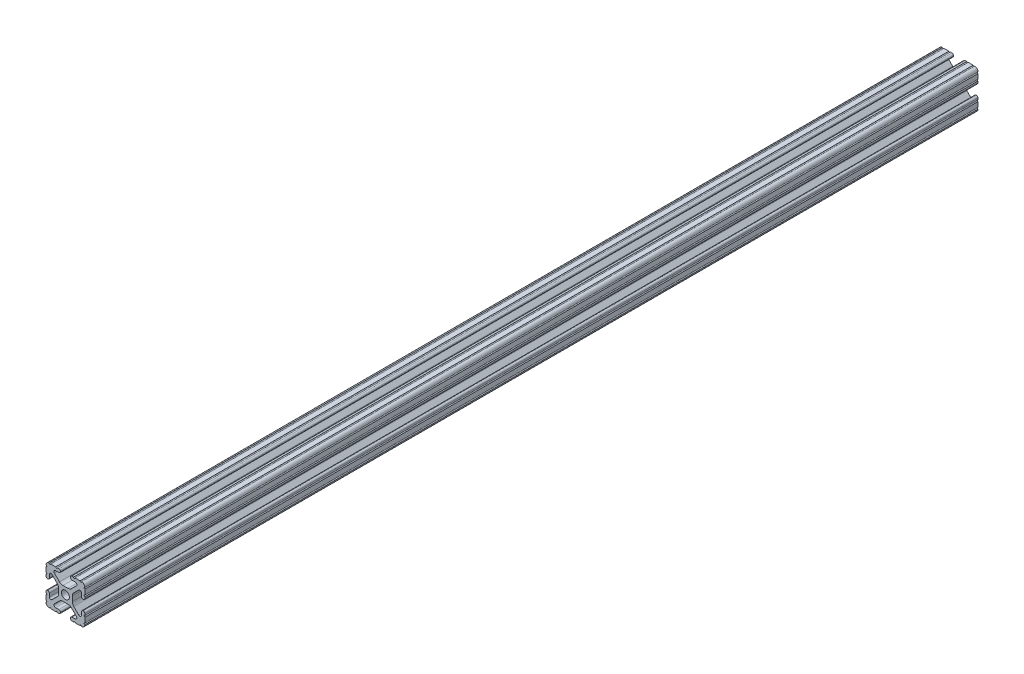
SolidWorks part; units mm, degrees
ref_plane "Front Plane" through (0, 0, 0) normal (0, 0, 1) x (1, 0, 0)
ref_plane "Top Plane" through (0, 0, 0) normal (0, 1, 0) x (1, 0, 0)
ref_plane "Right Plane" through (0, 0, 0) normal (1, 0, 0) x (0, 0, -1)
sketch "Sketch1" plane through (0, 0, 0) normal (0, 0, 1) x (1, 0, 0)
  line L88 (-7.1797, -8.6452) -> (-3.9523, -5.4237)
  line L89 (-1.7093, -4.4958) -> (1.7093, -4.4958)
  line L90 (3.9523, -5.4237) -> (7.1797, -8.6452)
  line L91 (6.4164, -10.4902) -> (4.2875, -10.4902)
  line L92 (3.2385, -11.5392) -> (3.2385, -11.651)
  line L93 (4.2875, -12.7) -> (5.3171, -12.7)
  line L94 (6.3331, -12.7) -> (9.5504, -12.7)
  line L95 (12.7, -9.5504) -> (12.7, -6.3331)
  line L96 (12.7, -5.3171) -> (12.7, -4.2875)
  line L97 (11.651, -3.2385) -> (11.5392, -3.2385)
  line L98 (10.4902, -4.2875) -> (10.4902, -6.4021)
  line L99 (8.7371, -7.1294) -> (5.441, -3.8408)
  line L100 (4.5085, -1.5932) -> (4.5085, 1.5932)
  line L101 (5.441, 3.8408) -> (8.7371, 7.1294)
  line L102 (10.4902, 6.4021) -> (10.4902, 4.2875)
  line L103 (11.5392, 3.2385) -> (11.651, 3.2385)
  line L104 (12.7, 4.2875) -> (12.7, 5.3171)
  line L105 (12.7, 6.3331) -> (12.7, 9.5504)
  line L106 (9.5504, 12.7) -> (6.3331, 12.7)
  line L107 (5.3171, 12.7) -> (4.2875, 12.7)
  line L108 (3.2385, 11.651) -> (3.2385, 11.5392)
  line L109 (4.2875, 10.4902) -> (6.4768, 10.4902)
  line L110 (7.207, 8.7244) -> (3.8983, 5.4232)
  line L111 (1.6558, 4.4958) -> (-1.6558, 4.4958)
  line L112 (-3.8983, 5.4232) -> (-7.207, 8.7244)
  line L113 (-6.4768, 10.4902) -> (-4.2875, 10.4902)
  line L114 (-3.2385, 11.5392) -> (-3.2385, 11.651)
  line L115 (-4.2875, 12.7) -> (-5.3171, 12.7)
  line L116 (-6.3331, 12.7) -> (-9.5504, 12.7)
  line L117 (-12.7, 9.5504) -> (-12.7, 6.3331)
  line L118 (-12.7, 5.3171) -> (-12.7, 4.2875)
  line L119 (-11.651, 3.2385) -> (-11.5392, 3.2385)
  line L120 (-10.4902, 4.2875) -> (-10.4902, 6.4021)
  line L121 (-8.7371, 7.1294) -> (-5.441, 3.8408)
  line L122 (-4.5085, 1.5932) -> (-4.5085, -1.5932)
  line L123 (-5.441, -3.8408) -> (-8.7371, -7.1294)
  line L124 (-10.4902, -6.4021) -> (-10.4902, -4.2875)
  line L125 (-11.5392, -3.2385) -> (-11.651, -3.2385)
  line L126 (-12.7, -4.2875) -> (-12.7, -5.3171)
  line L127 (-12.7, -6.3331) -> (-12.7, -9.5504)
  line L128 (-9.5504, -12.7) -> (-6.3331, -12.7)
  line L129 (-5.3171, -12.7) -> (-4.2875, -12.7)
  line L130 (-3.2385, -11.651) -> (-3.2385, -11.5392)
  line L131 (-4.2875, -10.4902) -> (-6.4164, -10.4902)
  circle A1 centre (0, 0) radius 2.6035
  arc A104 (-7.1797, -8.6452) -> (-6.4164, -10.4902) centre (-6.4164, -9.4098) ccw
  arc A105 (-1.7093, -4.4958) -> (-3.9523, -5.4237) centre (-1.7093, -7.6708) ccw
  arc A106 (3.9523, -5.4237) -> (1.7093, -4.4958) centre (1.7093, -7.6708) ccw
  arc A107 (6.4164, -10.4902) -> (7.1797, -8.6452) centre (6.4164, -9.4098) ccw
  arc A108 (4.2875, -10.4902) -> (3.2385, -11.5392) centre (4.2875, -11.5392) ccw
  arc A109 (3.2385, -11.651) -> (4.2875, -12.7) centre (4.2875, -11.651) ccw
  arc A110 (6.3331, -12.7) -> (5.3171, -12.7) centre (5.8251, -12.7) ccw
  arc A111 (10.5664, -12.6998) -> (9.5504, -12.7) centre (10.0584, -12.7) ccw
  arc A112 (10.5664, -12.6998) -> (12.6998, -10.5664) centre (10.5918, -10.5918) ccw
  arc A113 (12.7, -9.5504) -> (12.6998, -10.5664) centre (12.7, -10.0584) ccw
  arc A114 (12.7, -5.3171) -> (12.7, -6.3331) centre (12.7, -5.8251) ccw
  arc A115 (12.7, -4.2875) -> (11.651, -3.2385) centre (11.651, -4.2875) ccw
  arc A116 (11.5392, -3.2385) -> (10.4902, -4.2875) centre (11.5392, -4.2875) ccw
  arc A117 (8.7371, -7.1294) -> (10.4902, -6.4021) centre (9.4628, -6.4021) ccw
  arc A118 (4.5085, -1.5932) -> (5.441, -3.8408) centre (7.6835, -1.5932) ccw
  arc A119 (5.441, 3.8408) -> (4.5085, 1.5932) centre (7.6835, 1.5932) ccw
  arc A120 (10.4902, 6.4021) -> (8.7371, 7.1294) centre (9.4628, 6.4021) ccw
  arc A121 (10.4902, 4.2875) -> (11.5392, 3.2385) centre (11.5392, 4.2875) ccw
  arc A122 (11.651, 3.2385) -> (12.7, 4.2875) centre (11.651, 4.2875) ccw
  arc A123 (12.7, 6.3331) -> (12.7, 5.3171) centre (12.7, 5.8251) ccw
  arc A124 (12.6998, 10.5664) -> (12.7, 9.5504) centre (12.7, 10.0584) ccw
  arc A125 (12.6998, 10.5664) -> (10.5664, 12.6998) centre (10.5918, 10.5918) ccw
  arc A126 (9.5504, 12.7) -> (10.5664, 12.6998) centre (10.0584, 12.7) ccw
  arc A127 (5.3171, 12.7) -> (6.3331, 12.7) centre (5.8251, 12.7) ccw
  arc A128 (4.2875, 12.7) -> (3.2385, 11.651) centre (4.2875, 11.651) ccw
  arc A129 (3.2385, 11.5392) -> (4.2875, 10.4902) centre (4.2875, 11.5392) ccw
  arc A130 (7.207, 8.7244) -> (6.4768, 10.4902) centre (6.4768, 9.4563) ccw
  arc A131 (1.6558, 4.4958) -> (3.8983, 5.4232) centre (1.6558, 7.6708) ccw
  arc A132 (-3.8983, 5.4232) -> (-1.6558, 4.4958) centre (-1.6558, 7.6708) ccw
  arc A133 (-6.4768, 10.4902) -> (-7.207, 8.7244) centre (-6.4768, 9.4563) ccw
  arc A134 (-4.2875, 10.4902) -> (-3.2385, 11.5392) centre (-4.2875, 11.5392) ccw
  arc A135 (-3.2385, 11.651) -> (-4.2875, 12.7) centre (-4.2875, 11.651) ccw
  arc A136 (-6.3331, 12.7) -> (-5.3171, 12.7) centre (-5.8251, 12.7) ccw
  arc A137 (-10.5664, 12.6998) -> (-9.5504, 12.7) centre (-10.0584, 12.7) ccw
  arc A138 (-10.5664, 12.6998) -> (-12.6998, 10.5664) centre (-10.5918, 10.5918) ccw
  arc A139 (-12.7, 9.5504) -> (-12.6998, 10.5664) centre (-12.7, 10.0584) ccw
  arc A140 (-12.7, 5.3171) -> (-12.7, 6.3331) centre (-12.7, 5.8251) ccw
  arc A141 (-12.7, 4.2875) -> (-11.651, 3.2385) centre (-11.651, 4.2875) ccw
  arc A142 (-11.5392, 3.2385) -> (-10.4902, 4.2875) centre (-11.5392, 4.2875) ccw
  arc A143 (-8.7371, 7.1294) -> (-10.4902, 6.4021) centre (-9.4628, 6.4021) ccw
  arc A144 (-4.5085, 1.5932) -> (-5.441, 3.8408) centre (-7.6835, 1.5932) ccw
  arc A145 (-5.441, -3.8408) -> (-4.5085, -1.5932) centre (-7.6835, -1.5932) ccw
  arc A146 (-10.4902, -6.4021) -> (-8.7371, -7.1294) centre (-9.4628, -6.4021) ccw
  arc A147 (-10.4902, -4.2875) -> (-11.5392, -3.2385) centre (-11.5392, -4.2875) ccw
  arc A148 (-11.651, -3.2385) -> (-12.7, -4.2875) centre (-11.651, -4.2875) ccw
  arc A149 (-12.7, -6.3331) -> (-12.7, -5.3171) centre (-12.7, -5.8251) ccw
  arc A150 (-12.6998, -10.5664) -> (-12.7, -9.5504) centre (-12.7, -10.0584) ccw
  arc A151 (-12.6998, -10.5664) -> (-10.5664, -12.6998) centre (-10.5918, -10.5918) ccw
  arc A152 (-9.5504, -12.7) -> (-10.5664, -12.6998) centre (-10.0584, -12.7) ccw
  arc A153 (-5.3171, -12.7) -> (-6.3331, -12.7) centre (-5.8251, -12.7) ccw
  arc A154 (-4.2875, -12.7) -> (-3.2385, -11.651) centre (-4.2875, -11.651) ccw
  arc A155 (-3.2385, -11.5392) -> (-4.2875, -10.4902) centre (-4.2875, -11.5392) ccw
extrude "Boss-Extrude1" add sketch "Sketch1" along normal mid plane 584.2
